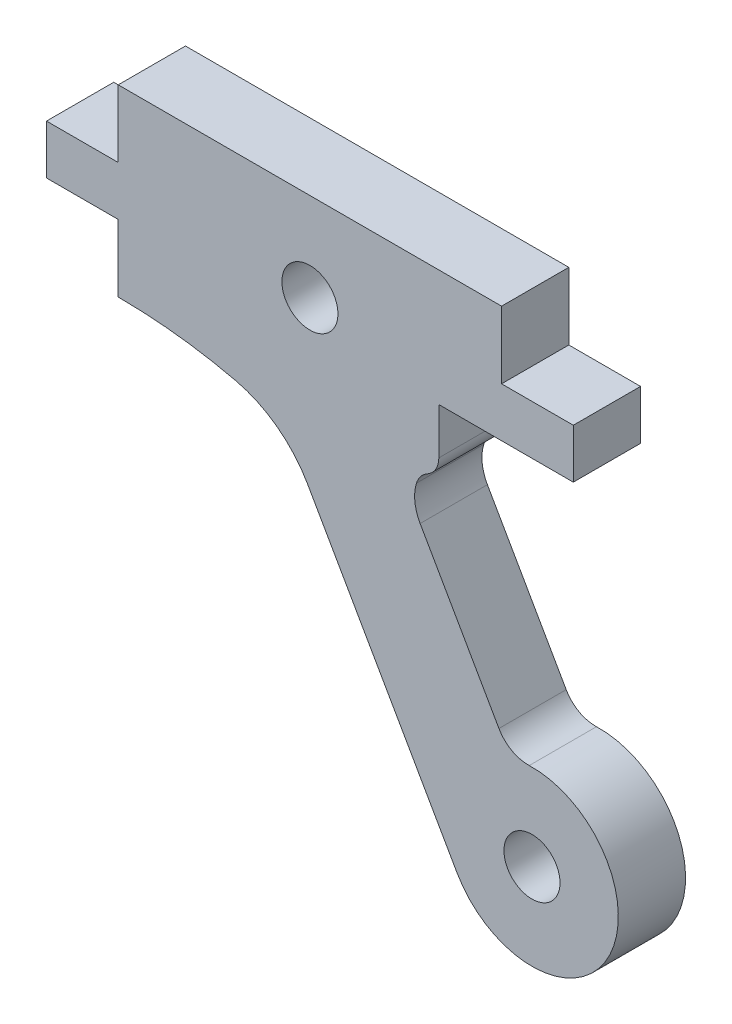
SolidWorks part; units mm, degrees
ref_plane "Front Plane" through (0, 0, 0) normal (0, 0, 1) x (1, 0, 0)
ref_plane "Top Plane" through (0, 0, 0) normal (0, 1, 0) x (1, 0, 0)
ref_plane "Right Plane" through (0, 0, 0) normal (1, 0, 0) x (0, 0, -1)
sketch "Sketch1" plane through (0, 0, 0) normal (0, 0, 1) x (1, 0, 0)
  line L42 (-8.55, 3.95) -> (-8.55, 0.95)
  line L43 (-8.55, 0.95) -> (-11.75, 0.95)
  line L44 (-11.75, 0.95) -> (-11.75, -1.25)
  line L45 (-11.75, -1.25) -> (-8.55, -1.25)
  line L46 (-8.55, -1.25) -> (-8.55, -4.25)
  line L47 (-0.1025, -7.25) -> (6.563, -18.9352)
  line L48 (8.4322, -12.4235) -> (4.9178, -6.2625)
  line L49 (5.75, -3.3118) -> (5.75, -1.25)
  line L50 (5.75, -1.25) -> (11.75, -1.25)
  line L51 (11.75, -1.25) -> (11.75, 0.95)
  line L52 (11.75, 0.95) -> (8.55, 0.95)
  line L53 (8.55, 0.95) -> (8.55, 3.95)
  line L54 (8.55, 3.95) -> (-8.55, 3.95)
  circle A3 centre (9.9072, -17.0276) radius 1.25
  circle A5 centre (0, 0) radius 1.25
  arc A19 (-3.3059, -4.8574) -> (-8.55, -4.25) centre (-8.55, -27.1931) ccw
  arc A20 (-0.1025, -7.25) -> (-3.3059, -4.8574) centre (-4.4499, -9.7299) ccw
  arc A21 (6.563, -18.9352) -> (9.7834, -13.1796) centre (9.9072, -17.0276) ccw
  arc A22 (8.4322, -12.4235) -> (9.7834, -13.1796) centre (9.7351, -11.6803) ccw
  arc A23 (4.756, -4.7824) -> (4.9178, -6.2625) centre (6.5417, -5.3361) ccw
  arc A24 (5.24, -4.1835) -> (4.756, -4.7824) centre (5.75, -5.0906) ccw
  arc A25 (5.24, -4.1835) -> (5.75, -3.3118) centre (4.75, -3.3118) ccw
  dimension "D4" = 17.1
  dimension "D5" = 22.9431
  dimension "D6" = 5.005
  dimension "D13" = 1
  dimension "D15" = 1.8696
  dimension "D16" = 3.85
  dimension "D17" = 2.5
  dimension "D18" = 1.5
  dimension "D19" = 2.5
  dimension "D3" = 6
  dimension "D7" = 13.4525
  dimension "D8" = 60.299
  dimension "D9" = 7.093
  dimension "D10" = 3
  dimension "D11" = 2.2
  dimension "D12" = 2.0618
  dimension "D14" = 1.0406
  dimension "D20" = 2.2
  dimension "D21" = 3
  dimension "D22" = 3
extrude "Boss-Extrude1" add sketch "Sketch1" along normal blind 3 contours L54 L42 L43 L44 L45 L46 A19 A20 L47 A21 A22 L48 A23 A24 A25 L49 L50 L51 L52 L53
